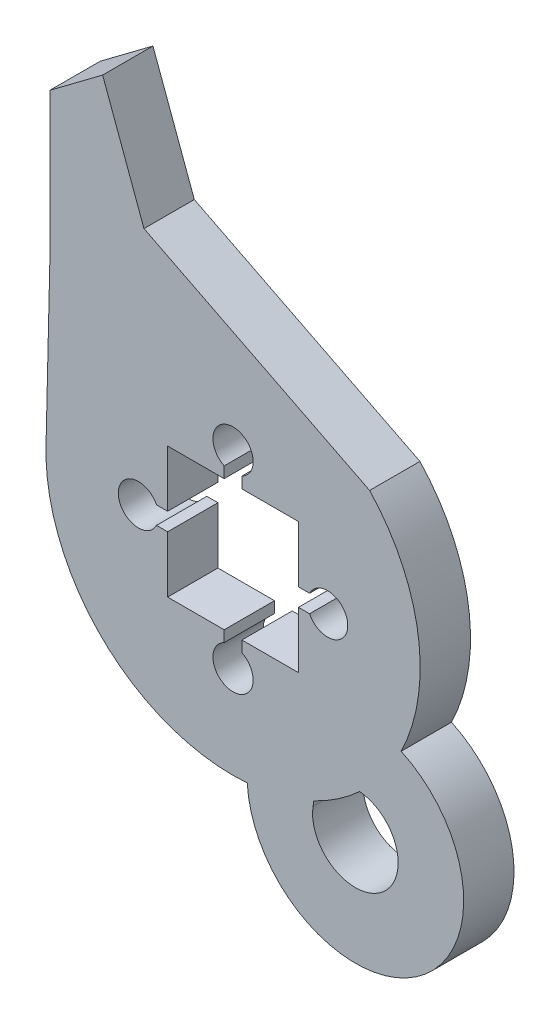
SolidWorks part; units mm, degrees
material "AISI 1020"
ref_plane "Front Plane" through (0, 0, 0) normal (0, 0, 1) x (1, 0, 0)
ref_plane "Top Plane" through (0, 0, 0) normal (0, 1, 0) x (1, 0, 0)
ref_plane "Right Plane" through (0, 0, 0) normal (1, 0, 0) x (0, 0, -1)
other "Center of Mass"
sketch "Sketch1" plane through (0, 0, 0) normal (0, 0, 1) x (1, 0, 0)
  line L0 (1.1176, -8.255) -> (8.255, -8.255)
  line L1 (-8.255, 8.255) -> (-1.1176, 8.255)
  line L2 (-8.255, 8.255) -> (-8.255, 1.1176)
  line L3 (-8.255, -8.255) -> (-1.1176, -8.255)
  line L4 (8.255, 8.255) -> (8.255, 1.1176)
  line L5 (8.255, -1.1176) -> (8.255, -8.255)
  line L6 (1.1176, 8.255) -> (8.255, 8.255)
  line L9 (-9.6571, 1.1176) -> (-8.255, 1.1176)
  line L11 (-9.6571, -1.1176) -> (-8.255, -1.1176)
  line L14 (-1.1176, 9.6571) -> (-1.1176, 8.255)
  line L16 (1.1176, 9.6571) -> (1.1176, 8.255)
  line L22 (-1.6292, 47.625) -> (-1.6292, 47.5971)
  line L25 (-1.6292, 47.625) -> (-1.6254, 47.5973) construction
  line L27 (-8.255, -1.1176) -> (-8.255, -8.255)
  line L28 (2.1529, 10.5902) -> (17.2334, 16.1434) construction
  line L29 (1.6254, 47.5973) -> (1.6292, 47.625) construction
  line L30 (-23.5874, 1.1116) -> (-1.1176, 9.3859) construction
  line L33 (17.2334, 16.1434) -> (-11.239, 30.5209)
  line L34 (-11.239, 30.5209) -> (-16.457, 44.6912)
  line L35 (-16.457, 44.6912) -> (-23.1206, 39.6938)
  line L36 (-23.1206, 39.6938) -> (-23.0807, 22.6234)
  line L37 (-23.0807, 22.6234) -> (-23.5874, 1.1116)
  line L38 (-23.0807, 22.6234) -> (-23.6135, 0) construction
  line L41 (-3.0398, 8.255) -> (-16.457, 44.6912) construction
  line L43 (-14.3858, 0.678) -> (-23.5874, 1.1116) construction
  line L45 (-1.1176, -8.255) -> (-1.1176, -9.6571)
  line L47 (1.1176, -8.255) -> (1.1176, -9.6571)
  line L48 (8.255, -1.1176) -> (9.6571, -1.1176)
  line L50 (8.255, 1.1176) -> (9.6571, 1.1176)
  arc A2 (-1.1176, -9.6571) -> (1.1176, -9.6571) centre (0, -11.938) ccw
  arc A3 (9.6571, -1.1176) -> (9.6571, 1.1176) centre (11.938, 0) ccw
  arc A23 (-1.6254, 47.5973) -> (-1.6292, 47.5971) centre (0, 0) ccw construction
  arc A24 (-23.5874, 1.1116) -> (17.2334, 16.1434) centre (0, 0) ccw
  arc A30 (-16.457, 44.6912) -> (-33.676, 33.676) centre (0, 0) ccw construction
  arc A31 (-9.6571, 1.1176) -> (-9.6571, -1.1176) centre (-11.938, 0) ccw
  arc A32 (1.1176, 9.6571) -> (-1.1176, 9.6571) centre (0, 11.938) ccw
  point P1 (0, 0)
  point P7 (0, 0)
  point P8 (0, 0)
  point P21 (-23.8044, 1.1176)
  point P26 (0, 0)
  point P28 (0, 35.6522)
  point P40 (0, 0)
  point P41 (0, 0)
  point P43 (0, -11.938)
  point P44 (0, 0)
  point P46 (0, 0)
  point P47 (0, 0)
  point P54 (0, 0)
  point P70 (0, 0)
  point P77 (0, 0)
  dimension "D2" = 95.25
  dimension "D4" = 5.08
  dimension "D1" = 16.51
  dimension "D3" = 11.938
  dimension "D5" = 2.2352
extrude "Boss-Extrude1" add sketch "Sketch1" along normal blind 6.35 contours L37 A24 L33 L34 L35 L36 A32 L16 L6 L4 L50 A3 L48 L5 L0 L47 A2 L45 L3 L27 L11 A31 L9 L2 L1 L14
sketch "Sketch2" plane through (0, 0, 0) normal (0, 0, -1) x (-1, 0, 0)
  arc A1 (-14.3665, -13.2844) -> (-6.0234, -21.2386) centre (-15.4356, -22.7584) ccw construction
  arc A2 (-13.9029, -9.1757) -> (-1.9415, -20.5795) centre (-15.4356, -22.7584) ccw
  arc A3 (-14.8302, -17.3931) -> (-10.1053, -21.8977) centre (-15.4356, -22.7584) ccw
  arc A4 (-14.8302, -17.3931) -> (-13.9029, -9.1757) centre (-14.3665, -13.2844) ccw
  arc A5 (-1.9415, -20.5795) -> (-10.1053, -21.8977) centre (-6.0234, -21.2386) ccw
  point P3 (-22.0145, -29.6589)
  point P8 (-24.1952, -16.8399)
  point P9 (-23.5585, -17.3857)
  point P10 (-22.8308, -18.3862)
  point P11 (-21.8302, -19.5687)
  point P12 (0, 0)
  point P13 (0, 0)
  point P14 (0, 0)
  point P15 (0, 0)
  point P16 (0, 0)
  point P17 (-6.7421, -19.7958)
  point P18 (-20.5568, -19.0229)
  point P19 (-14.5535, -10.018)
  point P20 (-17.976, -5.0287)
  point P22 (-6.1852, -17.7495)
  dimension "D1" = 15.4356
  dimension "D2" = 22.7584
extrude "Boss-Extrude3" add sketch "Sketch2" against normal blind 6.35 contours A2 A5 A3 A4
sketch "Sketch3" plane through (0, 0, 6.35) normal (0, 0, 1) x (1, 0, 0)
  line L0 (23.1081, -34.0708) -> (26.7325, -39.4147) construction
  circle A0 centre (0, 0) radius 47.625 construction
  arc A1 (1.7894, -23.5456) -> (21.2142, -10.371) centre (15.4356, -22.7584) ccw construction
